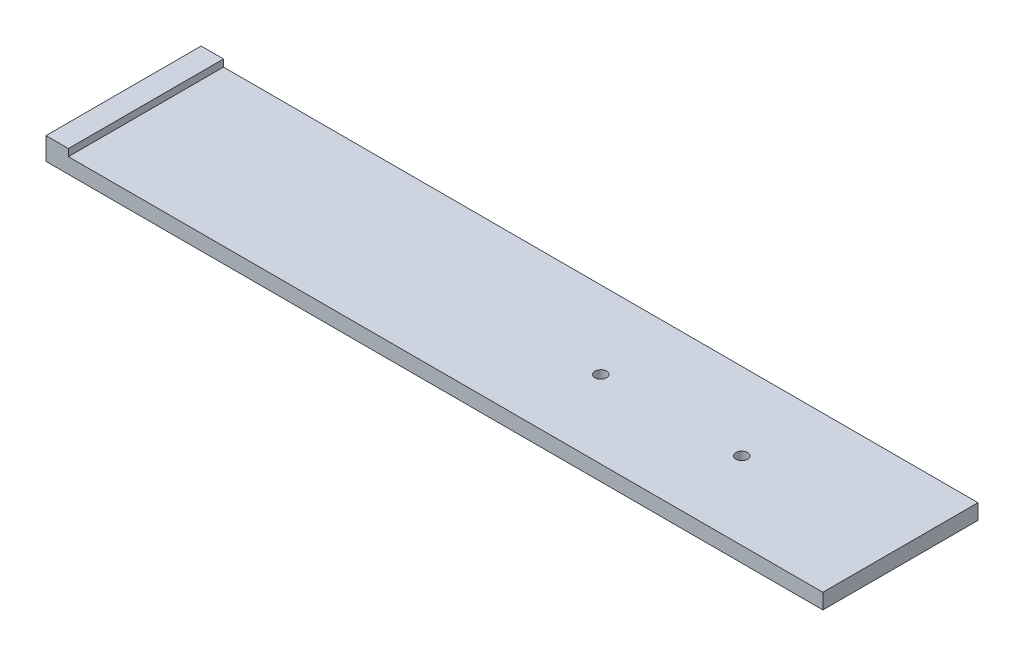
SolidWorks part; units mm, degrees
material "6061 Alloy"
ref_plane "Front" through (0, 0, 0) normal (0, 0, 1) x (1, 0, 0)
ref_plane "Top" through (0, 0, 0) normal (0, 1, 0) x (1, 0, 0)
ref_plane "Right" through (0, 0, 0) normal (1, 0, 0) x (0, 0, -1)
sketch "Sketch1" plane through (0, 0, 0) normal (0, 1, 0) x (1, 0, 0)
  line L1 (0, 0) -> (220.35, 0)
  line L2 (0, 0) -> (0, 44)
  line L3 (0, 44) -> (220.35, 44)
  line L4 (220.35, 0) -> (220.35, 44)
  dimension "D1" = 44
  dimension "D2" = 220.35
extrude "Boss-Extrude1" add sketch "Sketch1" along normal blind 4.35
sketch "Sketch2" plane through (0, 4.35, 0) normal (0, 1, 0) x (1, 0, 0)
  line L0 (220.35, 44) -> (0, 44) construction
  line L1 (0, 0) -> (6.35, 0)
  line L2 (0, 0) -> (0, 44)
  line L3 (0, 44) -> (6.35, 44)
  line L4 (6.35, 0) -> (6.35, 44)
  dimension "D1" = 6.35
extrude "Boss-Extrude2" add sketch "Sketch2" along normal blind 2
hole_wizard "M4x0.7 Tapped Hole2" positions "Sketch5" profile "Sketch6" tap size "M4x0.7" standard "ANSI Metric" end condition through all
sketch "Sketch5" plane through (0, 4.35, 0) normal (0, 1, 0) x (1, 0, 0)
  line L0 (220.35, 22) -> (135.35, 22) construction
  line L1 (220.35, 0) -> (220.35, 44) construction
  point P0 (135.35, 22)
  point P2 (175.35, 22)
  point P12 (0, 0)
  point P13 (0, 0)
  dimension "D1" = 85
  dimension "D2" = 40
sketch "Sketch6" plane through (135.35, 4.35, -22) normal (1, 0, 0) x (0, 0, 1)
  line L0 (0, 0) -> (0, 4.35)
  line L1 (0, 4.35) -> (1.65, 4.35)
  line L2 (1.65, 4.35) -> (1.65, 0)
  line L5 (1.65, 0) -> (0, 0)
  line L11 (0, -6.35) -> (0, 107.95) construction
  dimension "Thru Tap Drill Dia." = 3.3
  dimension "Thru Tap Drill Depth" = 4.35
cosmetic thread "Hole Thread1" parameters "D2"=4
cosmetic thread "Hole Thread2" parameters "D2"=4
